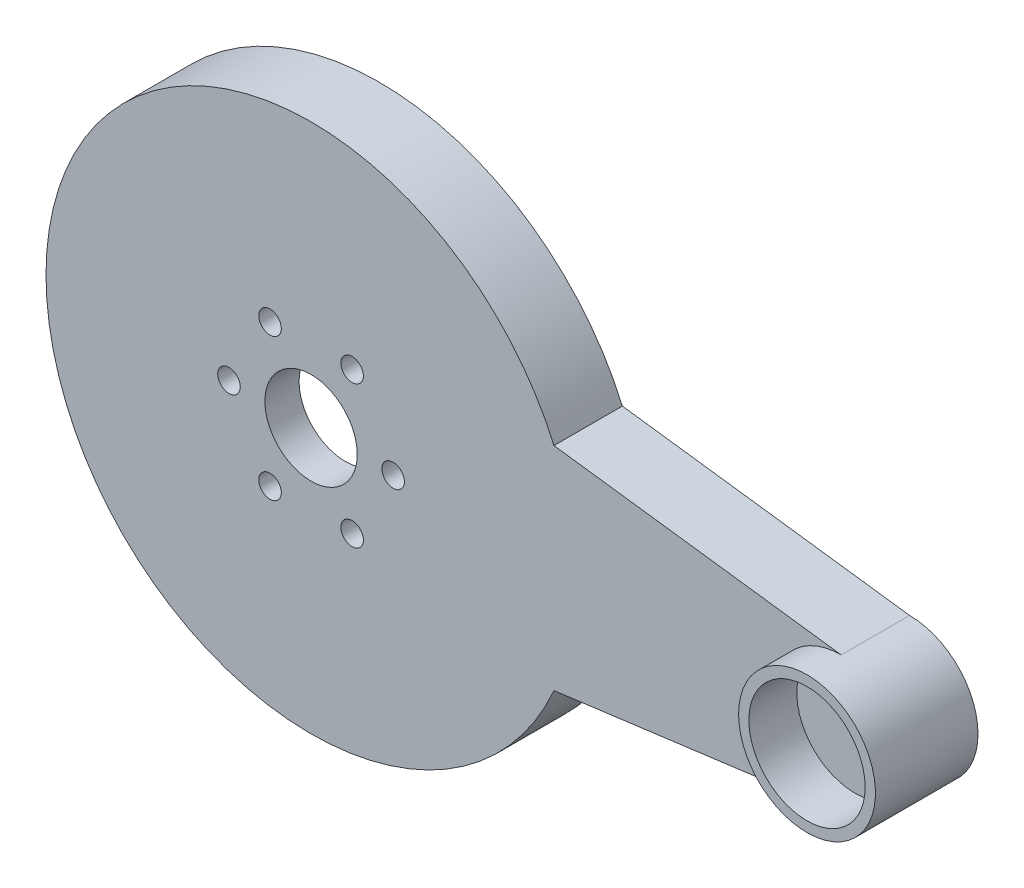
SolidWorks part; units mm, degrees
ref_plane "Front Plane" through (0, 0, 0) normal (0, 0, 1) x (1, 0, 0)
ref_plane "Top Plane" through (0, 0, 0) normal (0, 1, 0) x (1, 0, 0)
ref_plane "Right Plane" through (0, 0, 0) normal (1, 0, 0) x (0, 0, -1)
sketch "Sketch1" plane through (0, 0, 0) normal (0, 0, 1) x (1, 0, 0)
  line L0 (0, 0) -> (77.5, 0) construction
  line L1 (77.5, 10) -> (2.6026, 19.8299)
  line L2 (2.6026, 19.8299) -> (0, 0)
  line L3 (77.5, -10) -> (2.6026, -19.8299)
  line L4 (2.6026, -19.8299) -> (0, 0)
  circle A0 centre (0, 0) radius 38.75
  circle A1 centre (0, 0) radius 20
  circle A2 centre (77.5, 0) radius 10
  dimension "D1" = 77.5
  dimension "D2" = 40
  dimension "D4" = 20
  dimension "D3" = 77.5
extrude "Boss-Extrude1" add sketch "Sketch1" along normal blind 10
sketch "Sketch2" plane through (0, 0, 10) normal (0, 0, 1) x (1, 0, 0)
  circle A0 centre (0, 0) radius 6.75
  circle A1 centre (12, 0) radius 1.65
  circle A2 centre (6, -10.3923) radius 1.65
  circle A3 centre (-6, -10.3923) radius 1.65
  circle A4 centre (-12, 0) radius 1.65
  circle A5 centre (-6, 10.3923) radius 1.65
  circle A6 centre (6, 10.3923) radius 1.65
  dimension "D1" = 13.5
  dimension "D2" = 3.3
  dimension "D3" = 12
  dimension "D4" = 6
extrude "Cut-Extrude1" cut sketch "Sketch2" against normal through all
sketch "Sketch3" plane through (0, 0, 0) normal (0, 1, 0) x (1, 0, 0)
  line L0 (15, -5) -> (20, 0)
  line L1 (0, 0) -> (15, 0)
  line L2 (0, 0) -> (0, -5)
  line L3 (0, -5) -> (15, -5)
  line L4 (15, 0) -> (15, -5)
  line L5 (35.5102, 0) -> (-38.75, 0) construction
  line L6 (20, 0) -> (15, 0)
  dimension "D1" = 15
  dimension "D2" = 5
  dimension "D3" = 5
revolve "Cut-Revolve1" cut sketch "Sketch3" angle 360 about L2
sketch "Sketch4" plane through (0, 0, 0) normal (0, 0, -1) x (-1, 0, 0)
  circle A0 centre (-77.5, 0) radius 10
extrude "Boss-Extrude2" add sketch "Sketch4" against normal blind 15
sketch "Sketch5" plane through (0, 0, 15) normal (0, 0, 1) x (1, 0, 0)
  circle A0 centre (77.5, 0) radius 8.5
  dimension "D1" = 17
extrude "Cut-Extrude2" cut sketch "Sketch5" against normal blind 7
